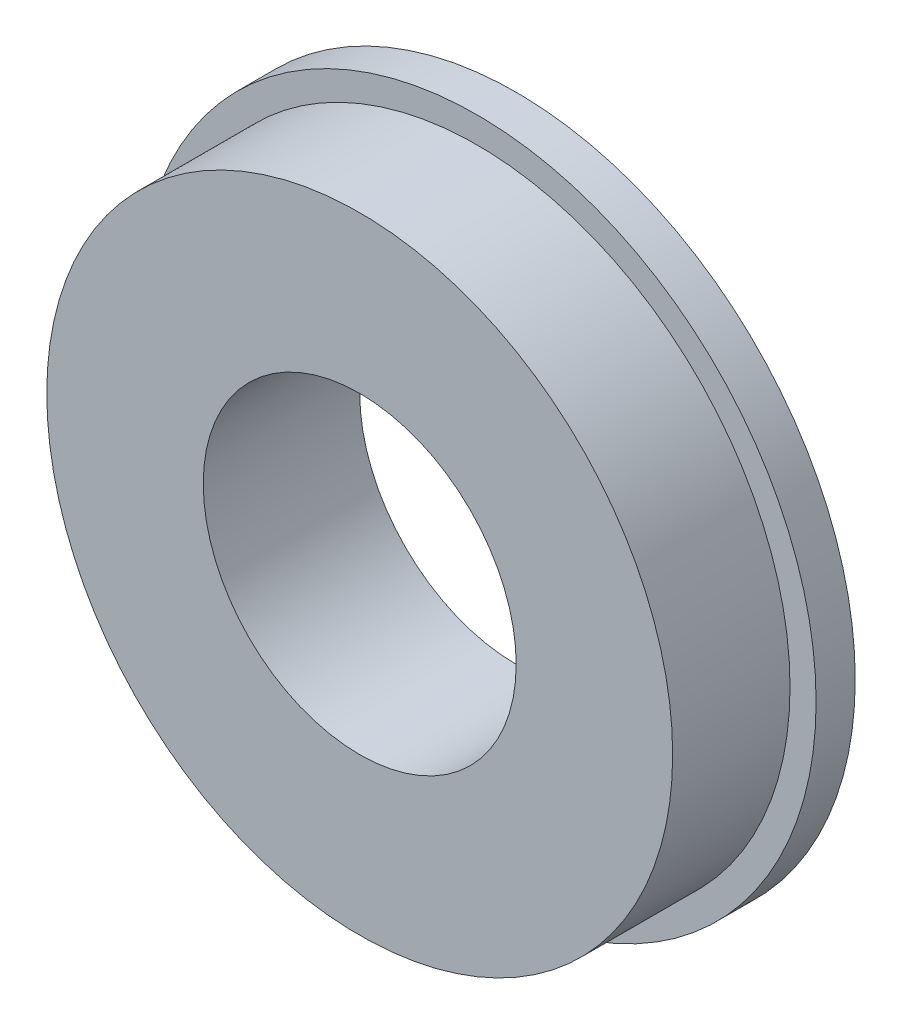
SolidWorks part; units mm, degrees
ref_plane "Front Plane" through (0, 0, 0) normal (0, 0, 1) x (1, 0, 0)
ref_plane "Top Plane" through (0, 0, 0) normal (0, 1, 0) x (1, 0, 0)
ref_plane "Right Plane" through (0, 0, 0) normal (1, 0, 0) x (0, 0, -1)
sketch "Sketch1" plane through (0, 0, 0) normal (0, 0, 1) x (1, 0, 0)
  circle A0 centre (0, 0) radius 13
  dimension "D1" = 26
extrude "Boss-Extrude1" add sketch "Sketch1" along normal blind 1.5
sketch "Sketch2" plane through (0, 0, 1.5) normal (0, 0, 1) x (1, 0, 0)
  circle A0 centre (0, 0) radius 12
  dimension "D1" = 24
extrude "Boss-Extrude2" add sketch "Sketch2" along normal blind 4.5
sketch "Sketch3" plane through (0, 0, 6) normal (0, 0, 1) x (1, 0, 0)
  circle A0 centre (0, 0) radius 6
  dimension "D1" = 12
extrude "Cut-Extrude1" cut sketch "Sketch3" against normal through all
